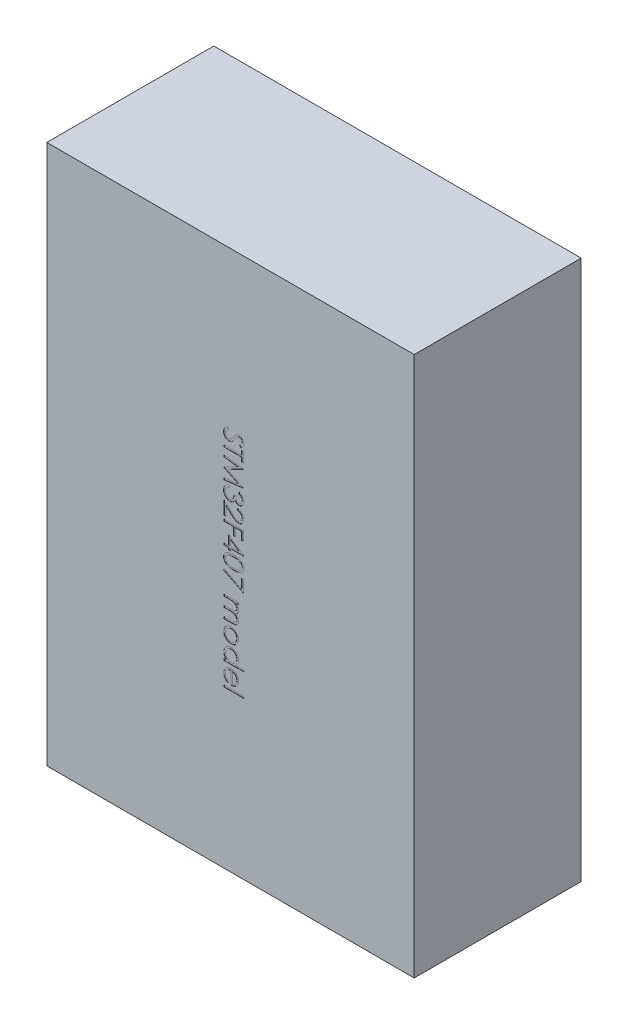
SolidWorks part; units mm, degrees
ref_plane "정면" through (0, 0, 0) normal (0, 0, 1) x (1, 0, 0)
ref_plane "윗면" through (0, 0, 0) normal (0, 1, 0) x (1, 0, 0)
ref_plane "우측면" through (0, 0, 0) normal (1, 0, 0) x (0, 0, -1)
sketch "스케치1" plane through (0, 0, 0) normal (0, 0, 1) x (1, 0, 0)
  line L1 (-33, 48.5) -> (33, 48.5)
  line L2 (-33, 48.5) -> (-33, -48.5)
  line L3 (-33, -48.5) -> (33, -48.5)
  line L4 (33, 48.5) -> (33, -48.5)
  line L5 (-33, 48.5) -> (33, -48.5) construction
  line L6 (-33, -48.5) -> (33, 48.5) construction
  point P0 (0, 0)
  dimension "D1" = 97
  dimension "D2" = 66
extrude "보스-돌출1" add sketch "스케치1" along normal blind 30
sketch "스케치2" plane through (0, 0, 30) normal (0, 0, 1) x (1, 0, 0)
  line L0 (-1.1554, 48.5) -> (-1.1554, -48.5) construction
  line L1 (33, 48.5) -> (-33, 48.5) construction
  line L2 (-33, -48.5) -> (33, -48.5) construction
  text T0 "STM32F407 model"
extrude "컷-돌출1" cut sketch "스케치2" against normal blind 0.04
